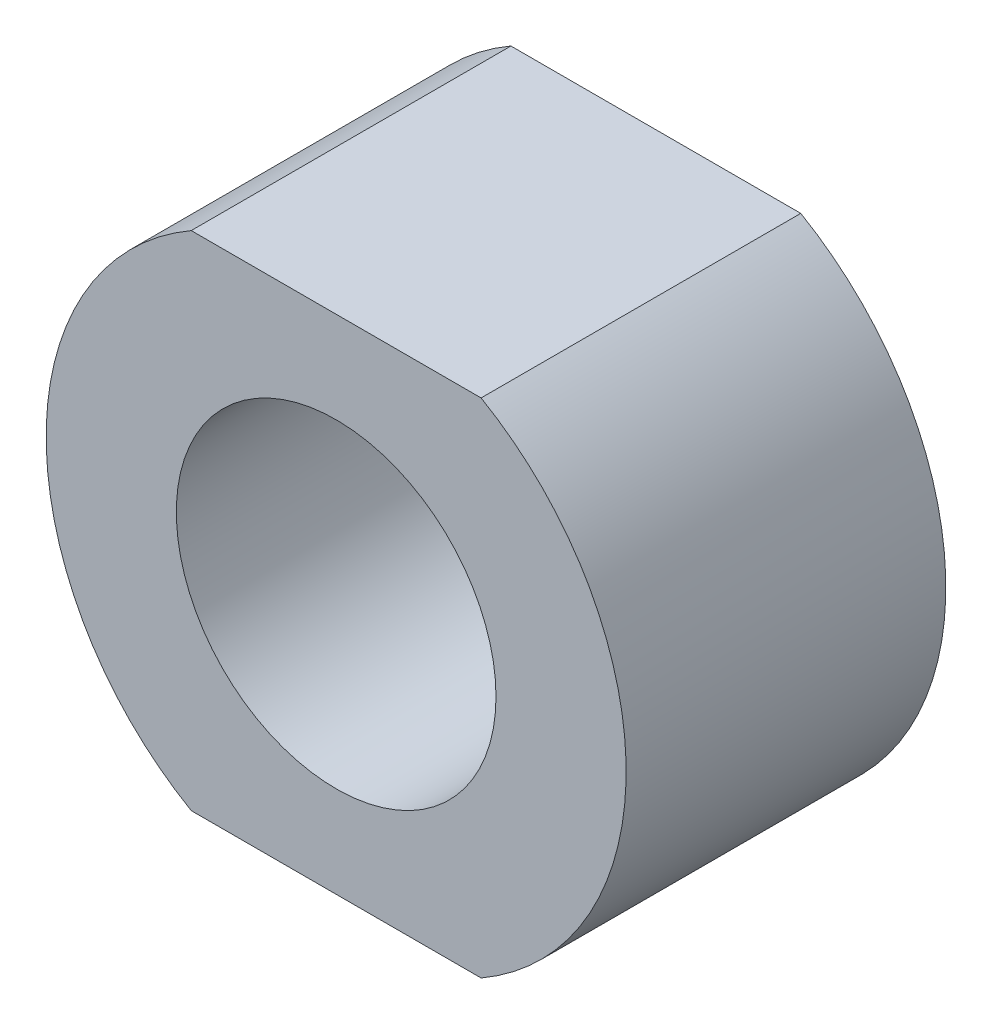
SolidWorks part; units mm, degrees
ref_plane "Plan de face" through (0, 0, 0) normal (0, 0, 1) x (1, 0, 0)
ref_plane "Plan de dessus" through (0, 0, 0) normal (0, 1, 0) x (1, 0, 0)
ref_plane "Plan de droite" through (0, 0, 0) normal (1, 0, 0) x (0, 0, -1)
sketch "Esquisse1" plane through (0, 0, 0) normal (0, 0, 1) x (1, 0, 0)
  circle A0 centre (0, 0) radius 6.35
  dimension "D1" = 12.7
extrude "Boss.-Extru.1" add sketch "Esquisse1" along normal blind 7
sketch "Esquisse2" plane through (0, 0, 7) normal (0, 0, 1) x (1, 0, 0)
  circle A0 centre (0, 0) radius 3.5
  dimension "D1" = 7
extrude "Enlèv. mat.-Extru.1" cut sketch "Esquisse2" against normal blind 7
sketch "Esquisse3" plane through (0, 0, 7) normal (0, 0, 1) x (1, 0, 0)
  line L0 (0, 0) -> (1.9269, 0) construction
  line L1 (-5.0202, 7.3762) -> (5.6963, 7.3762)
  line L2 (-5.0202, 7.3762) -> (-5.0202, 5.5)
  line L3 (-5.0202, 5.5) -> (5.6963, 5.5)
  line L4 (5.6963, 7.3762) -> (5.6963, 5.5)
  line L5 (-5.0202, -5.5) -> (5.6963, -5.5)
  line L6 (5.6963, -7.3762) -> (5.6963, -5.5)
  line L7 (-5.0202, -7.3762) -> (5.6963, -7.3762)
  line L8 (-5.0202, -7.3762) -> (-5.0202, -5.5)
  dimension "D1" = 5.5
extrude "Enlèv. mat.-Extru.2" cut sketch "Esquisse3" against normal through all
